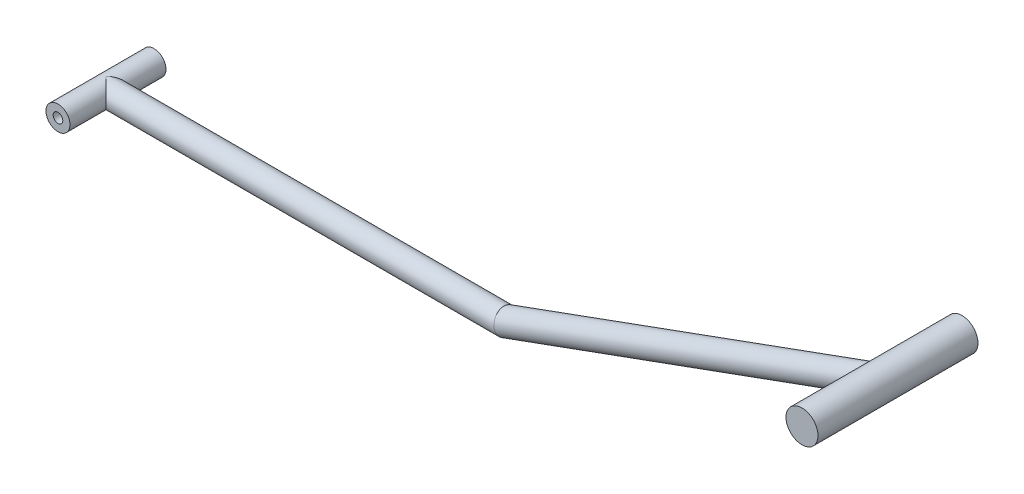
SolidWorks part; units mm, degrees
material "Plain Carbon Steel"
ref_plane "Front Plane" through (0, 0, 0) normal (0, 0, 1) x (1, 0, 0)
ref_plane "Top Plane" through (0, 0, 0) normal (0, 1, 0) x (1, 0, 0)
ref_plane "Right Plane" through (0, 0, 0) normal (1, 0, 0) x (0, 0, -1)
sketch "Sketch1" plane through (0, 0, 0) normal (0, 0, 1) x (1, 0, 0)
  circle A0 centre (0, 0) radius 6
  circle A1 centre (0, 0) radius 15
  dimension "D1" = 12
  dimension "D2" = 30
extrude "Boss-Extrude1" add sketch "Sketch1" along normal mid plane 120
sketch "Sketch2" plane through (0, 0, 0) normal (1, 0, 0) x (0, 0, -1)
  circle A0 centre (0, 0) radius 15
  dimension "D1" = 30
sketch "Sketch3" plane through (0, 0, 0) normal (0, 0, 1) x (1, 0, 0)
  line L0 (0, 0) -> (500, 0)
  line L1 (0, -15) -> (0, 15) construction
  line L2 (500, 0) -> (969.8463, 171.0101)
  dimension "D1" = 500
  dimension "D2" = 500
  dimension "D3" = 160
sweep "Sweep1" add profiles "Sketch2" path "Sketch3"
sketch "Sketch5" plane through (0, 0, 0) normal (0, 0, 1) x (1, 0, 0)
  line L1 (974.9766, 156.9147) -> (964.716, 185.1055) construction
  circle A0 centre (969.8463, 171.0101) radius 20
  dimension "D1" = 40
extrude "Boss-Extrude2" add sketch "Sketch5" along normal mid plane 200
